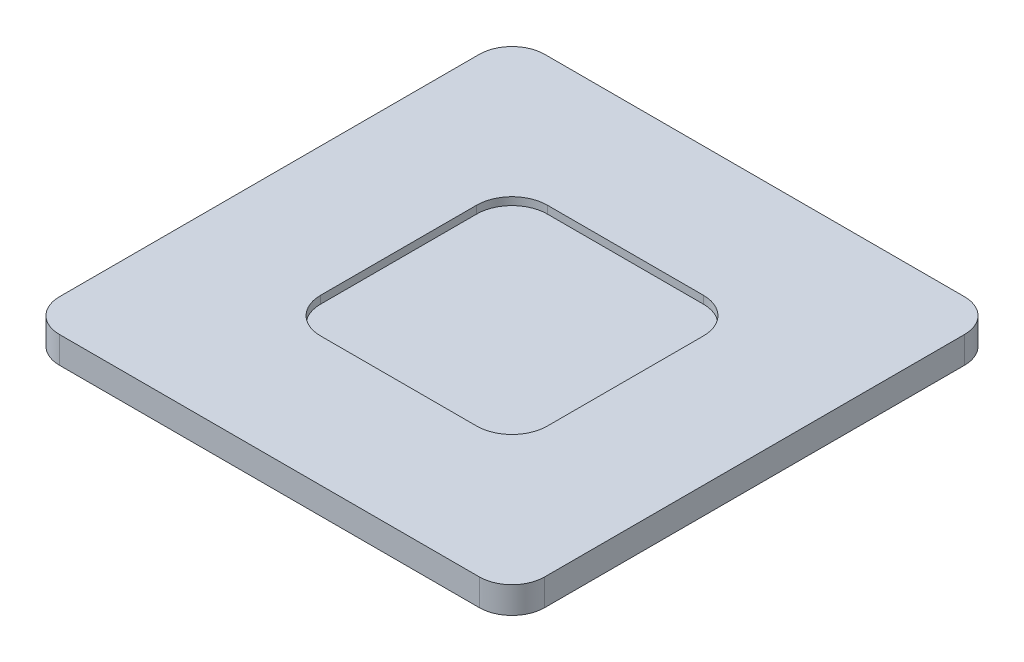
SolidWorks part; units mm, degrees
ref_plane "Front Plane" through (0, 0, 0) normal (0, 0, 1) x (1, 0, 0)
ref_plane "Top Plane" through (0, 0, 0) normal (0, 1, 0) x (1, 0, 0)
ref_plane "Right Plane" through (0, 0, 0) normal (1, 0, 0) x (0, 0, -1)
sketch "Sketch3" plane through (0, 0, 0) normal (0, 1, 0) x (1, 0, 0)
  line L1 (0, 0) -> (47.625, 0) construction
  line L3 (0, 47.625) -> (47.625, 47.625) construction
  line L8 (0, 47.625) -> (0, 0) construction
  line L9 (47.625, 47.625) -> (47.625, 0) construction
  line L14 (0.254, 0.254) -> (47.371, 0.254)
  line L15 (47.371, 47.371) -> (47.371, 0.254)
  line L16 (0.254, 47.371) -> (47.371, 47.371)
  line L17 (0.254, 47.371) -> (0.254, 0.254)
  point P9 (0, 47.625)
  point P12 (0, 0)
  dimension "D2" = 0.254
  dimension "D1" = 47.625
extrude "Boss-Extrude1" add sketch "Sketch3" along normal blind 2.5908
fillet "Fillet2" radius 3.175 4 edges at (0.254, 1.2954, -0.254) (47.371, 1.2954, -0.254) (47.371, 1.2954, -47.371) (0.254, 1.2954, -47.371)
sketch "Sketch5" plane through (0, 2.5908, 0) normal (0, 1, 0) x (1, 0, 0)
  line L0 (31.3875, 34.5625) -> (16.2375, 34.5625) construction
  line L1 (13.0625, 31.3875) -> (13.0625, 16.2375) construction
  line L2 (16.2375, 13.0625) -> (31.3875, 13.0625) construction
  line L3 (34.5625, 16.2375) -> (34.5625, 31.3875) construction
  line L4 (23.8125, 34.5625) -> (23.8125, 47.371) construction
  line L5 (44.196, 47.371) -> (3.429, 47.371) construction
  line L6 (34.5625, 23.8125) -> (47.371, 23.8125) construction
  line L7 (47.371, 3.429) -> (47.371, 44.196) construction
  line L8 (31.3875, 34.8165) -> (16.2375, 34.8165)
  line L9 (12.8085, 31.3875) -> (12.8085, 16.2375)
  line L10 (16.2375, 12.8085) -> (31.3875, 12.8085)
  line L11 (34.8165, 16.2375) -> (34.8165, 31.3875)
  arc A0 (16.2375, 34.5625) -> (13.0625, 31.3875) centre (16.2375, 31.3875) ccw construction
  arc A1 (13.0625, 16.2375) -> (16.2375, 13.0625) centre (16.2375, 16.2375) ccw construction
  arc A2 (31.3875, 13.0625) -> (34.5625, 16.2375) centre (31.3875, 16.2375) ccw construction
  arc A3 (34.5625, 31.3875) -> (31.3875, 34.5625) centre (31.3875, 31.3875) ccw construction
  arc A4 (16.2375, 34.8165) -> (12.8085, 31.3875) centre (16.2375, 31.3875) ccw
  arc A5 (12.8085, 16.2375) -> (16.2375, 12.8085) centre (16.2375, 16.2375) ccw
  arc A6 (31.3875, 12.8085) -> (34.8165, 16.2375) centre (31.3875, 16.2375) ccw
  arc A7 (34.8165, 31.3875) -> (31.3875, 34.8165) centre (31.3875, 31.3875) ccw
  point P20 (23.8125, 35.8125)
  dimension "D3" = 3.175
  dimension "D1" = 21.5
  dimension "D2" = 21.5
  dimension "D4" = 0.254
extrude "Cut-Extrude1" cut sketch "Sketch5" against normal blind 0.75
